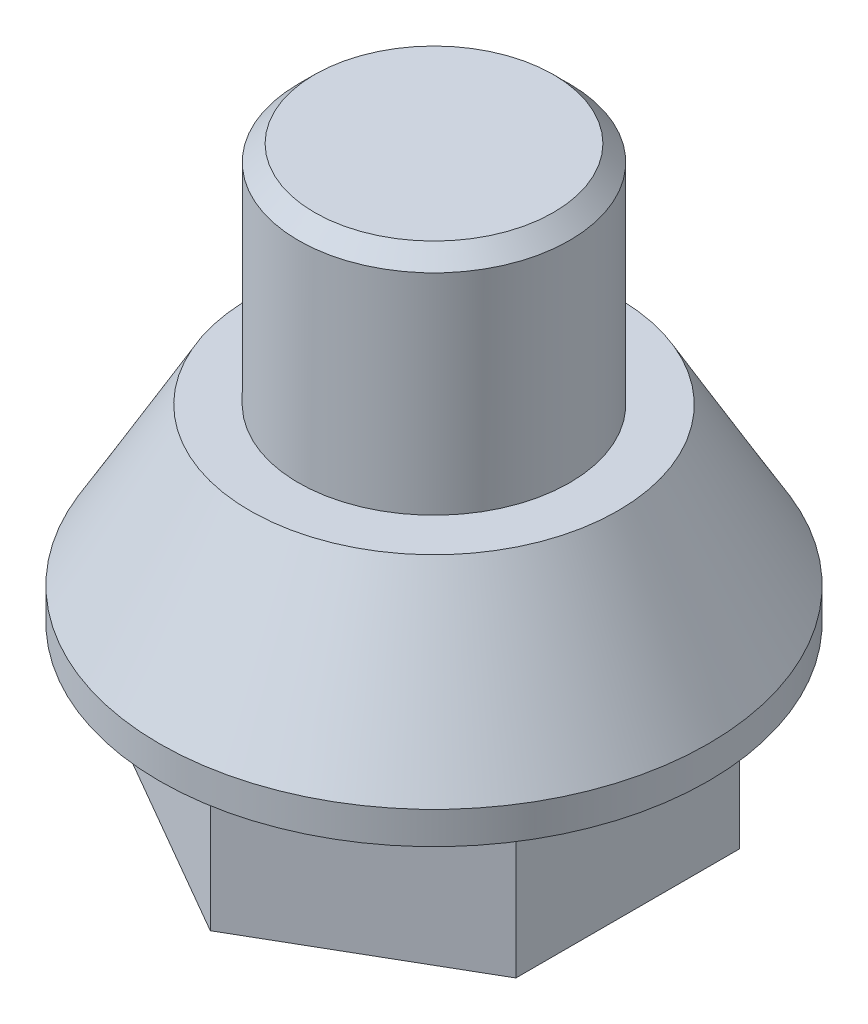
SolidWorks part; units mm, degrees
ref_plane "Front Plane" through (0, 0, 0) normal (0, 0, 1) x (1, 0, 0)
ref_plane "Top Plane" through (0, 0, 0) normal (0, 1, 0) x (1, 0, 0)
ref_plane "Right Plane" through (0, 0, 0) normal (1, 0, 0) x (0, 0, -1)
sketch "Sketch1" plane through (0, 0, 0) normal (0, 1, 0) x (1, 0, 0)
  line L0 (0, 6.9282) -> (0, -6.9282) construction
  line L1 (-6, -3.4641) -> (6, 3.4641) construction
  line L2 (6, -3.4641) -> (-6, 3.4641) construction
  line L3 (0, 6.9282) -> (6, 3.4641)
  line L4 (6, 3.4641) -> (6, -3.4641)
  line L5 (6, -3.4641) -> (0, -6.9282)
  line L6 (0, -6.9282) -> (-6, -3.4641)
  line L7 (-6, -3.4641) -> (-6, 3.4641)
  line L8 (-6, 3.4641) -> (0, 6.9282)
  dimension "D1" = 60
  dimension "D2" = 60
  dimension "D3" = 12
extrude "Boss-Extrude1" add sketch "Sketch1" along normal blind 4.8
sketch "Sketch2" plane through (0, 4.8, 0) normal (0, 1, 0) x (1, 0, 0)
  circle A0 centre (0, 0) radius 8.5
  dimension "D1" = 17
extrude "Boss-Extrude2" add sketch "Sketch2" along normal blind 1
sketch "Sketch3" plane through (0, 0, 0) normal (0, 0, 1) x (1, 0, 0)
  line L0 (0, 5.8) -> (8.5, 5.8)
  line L1 (8.5, 5.8) -> (5.7, 10.6497)
  line L2 (5.7, 10.6497) -> (4.2, 10.6497)
  line L3 (4.2, 10.6497) -> (4.2, 17.6497)
  line L4 (4.2, 17.6497) -> (0, 17.6497)
  line L5 (0, 5.8) -> (0, 17.6497)
  line L6 (8.5, 5.8) -> (-8.5, 5.8) construction
  dimension "D1" = 4.2
  dimension "D2" = 1.5
  dimension "D3" = 7
  dimension "D4" = 60
revolve "Revolve1" add sketch "Sketch3" angle 360 about L5
chamfer "Chamfer1" distance 0.5 angle 45 1 edges at (4.2, 17.6497, 0)
